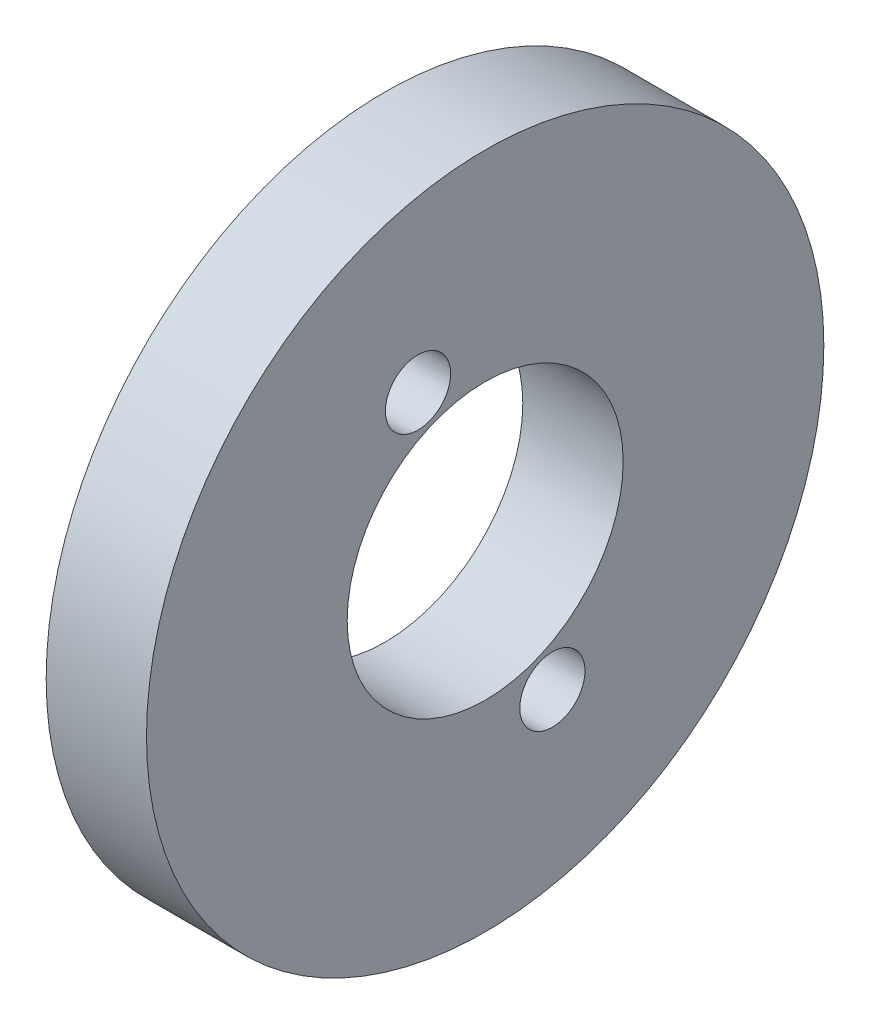
SolidWorks part; units mm, degrees
ref_plane "Front Plane" through (0, 0, 0) normal (0, 0, 1) x (1, 0, 0)
ref_plane "Top Plane" through (0, 0, 0) normal (0, 1, 0) x (1, 0, 0)
ref_plane "Right Plane" through (0, 0, 0) normal (1, 0, 0) x (0, 0, -1)
sketch "Axial profile (mm)" plane through (0, 0, 0) normal (0, 0, 1) x (1, 0, 0)
  line L0 (-110, 0) -> (75, 0) construction
  line L1 (135.7, 11) -> (143.7, 11)
  line L2 (143.7, 11) -> (143.7, 27)
  line L3 (143.7, 27) -> (135.7, 27)
  line L4 (135.7, 27) -> (135.7, 11)
revolve "Full revolution" add sketch "Axial profile (mm)" angle 360 about L0
sketch "Sketch2" plane through (0, 0, 0) normal (1, 0, 0) x (0, 0, -1)
  circle A0 centre (-5.3576, 12.9343) radius 2.6
  circle A1 centre (5.3576, -12.9343) radius 2.6
extrude "Axial holes" cut sketch "Sketch2" against normal through all and the other way through all
